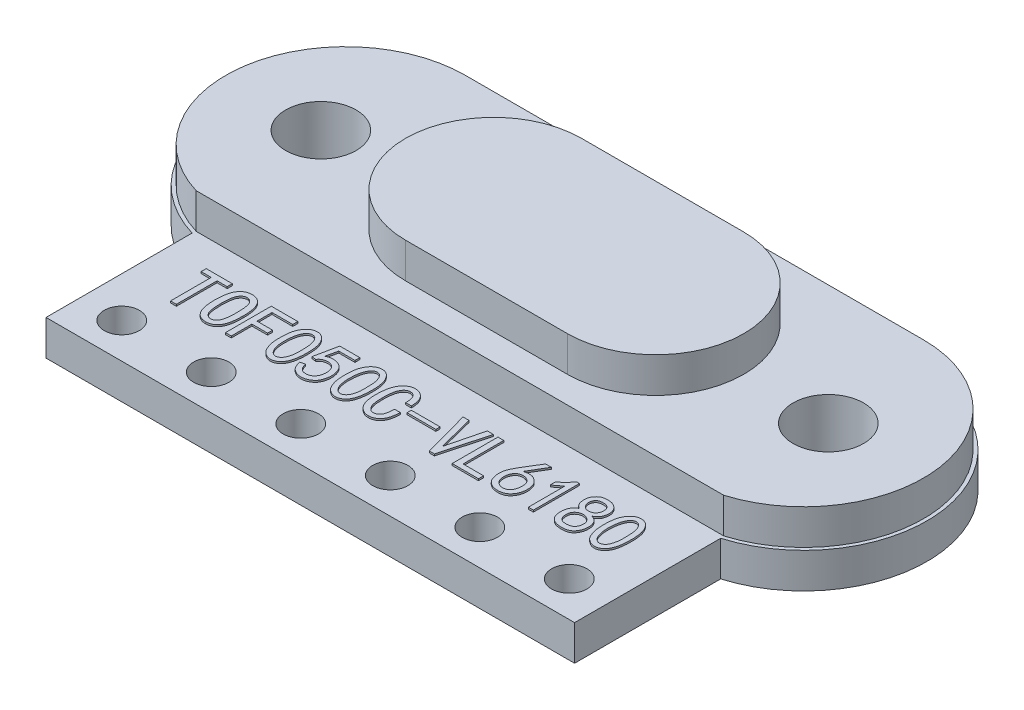
SolidWorks part; units mm, degrees
ref_plane "前视基准面" through (0, 0, 0) normal (0, 0, 1) x (1, 0, 0)
ref_plane "上视基准面" through (0, 0, 0) normal (0, 1, 0) x (1, 0, 0)
ref_plane "右视基准面" through (0, 0, 0) normal (1, 0, 0) x (0, 0, -1)
other "Configuration Table"
sketch "草图1" plane through (0, 0, 0) normal (0, 1, 0) x (1, 0, 0)
  line L0 (-6.5, 0) -> (6.5, 0) construction
  line L1 (-6.5, 3.5) -> (6.5, 3.5)
  line L3 (-7.5, -7.5) -> (7.5, -7.5)
  line L4 (7.5, -7.5) -> (7.5, -3.3541)
  line L5 (-7.5, -7.5) -> (-7.5, -3.3541)
  arc A0 (-6.5, 3.5) -> (-7.5, -3.3541) centre (-6.5, 0) ccw
  arc A1 (7.5, -3.3541) -> (6.5, 3.5) centre (6.5, 0) ccw
  point P2 (0, 0)
  point P13 (0, -7.5)
  dimension "D1" = 3.5
  dimension "D2" = 13
  dimension "D3" = 15
  dimension "D4" = 11
extrude "凸台-拉伸1" add sketch "草图1" along normal blind 1
sketch "草图2" plane through (0, 1, 0) normal (0, 1, 0) x (1, 0, 0)
  line L0 (6.5, 3.5) -> (-6.5, 3.5) construction
  line L1 (-7.4853, -3.2541) -> (7.4853, -3.2541)
  line L2 (6.5, 3.5) -> (-6.5, 3.5) construction
  line L3 (-7.5, -3.3541) -> (7.5, -3.3541) construction
  line L4 (6.5, 3.4) -> (-6.5, 3.4)
  arc A0 (-6.5, 3.5) -> (-7.5, -3.3541) centre (-6.5, 0) ccw construction
  arc A1 (7.5, -3.3541) -> (6.5, 3.5) centre (6.5, 0) ccw construction
  arc A2 (7.5, -3.3541) -> (6.5, 3.5) centre (6.5, 0) ccw construction
  arc A3 (-6.5, 3.5) -> (-7.5, -3.3541) centre (-6.5, 0) ccw construction
  arc A4 (7.4853, -3.2541) -> (6.5, 3.4) centre (6.5, 0) ccw
  arc A5 (-6.5, 3.4) -> (-7.4853, -3.2541) centre (-6.5, 0) ccw
  dimension "D1" = 0.1
extrude "凸台-拉伸3" add sketch "草图2" along normal blind 1
sketch "草图3" plane through (0, 2, 0) normal (0, 1, 0) x (1, 0, 0)
  line L0 (-2.3, 0) -> (2.3, 0) construction
  line L1 (-2.3, 2.5) -> (2.3, 2.5)
  line L2 (-2.3, -2.5) -> (2.3, -2.5)
  arc A0 (-2.3, 2.5) -> (-2.3, -2.5) centre (-2.3, 0) ccw
  arc A1 (2.3, -2.5) -> (2.3, 2.5) centre (2.3, 0) ccw
  point P2 (0, 0)
  dimension "D1" = 2.5
  dimension "D2" = 4.6
extrude "凸台-拉伸4" add sketch "草图3" along normal blind 1
sketch "草图4" plane through (0, 0, 0) normal (0, -1, 0) x (1, 0, 0)
  line L0 (-7.2, 0) -> (7.2, 0) construction
  circle A0 centre (-7.2, 0) radius 1
  circle A1 centre (7.2, 0) radius 1
  point P4 (0, 0)
  dimension "D2" = 2
  dimension "D3" = 2
  dimension "D1" = 14.4
extrude "切除-拉伸1" cut sketch "草图4" against normal through all
sketch "草图5" plane through (0, 1, 0) normal (0, 1, 0) x (1, 0, 0)
  line L0 (0, 0) -> (0, -7.0853) construction
  circle A0 centre (-6.35, -6.5) radius 0.5
  circle A1 centre (-3.81, -6.5) radius 0.5
  circle A2 centre (-1.27, -6.5) radius 0.5
  circle A3 centre (1.27, -6.5) radius 0.5
  circle A4 centre (3.81, -6.5) radius 0.5
  circle A5 centre (6.35, -6.5) radius 0.5
  dimension "D1" = 6
  dimension "D2" = 1
  dimension "D3" = 2.54
extrude "切除-拉伸2" cut sketch "草图5" against normal through all
sketch "草图6" plane through (0, 1, 0) normal (0, 1, 0) x (1, 0, 0)
  text T0 "TOF050C-VL6180" font "黑体" height 1.3
extrude "凸台-拉伸5" add sketch "草图6" along normal blind 0.05
